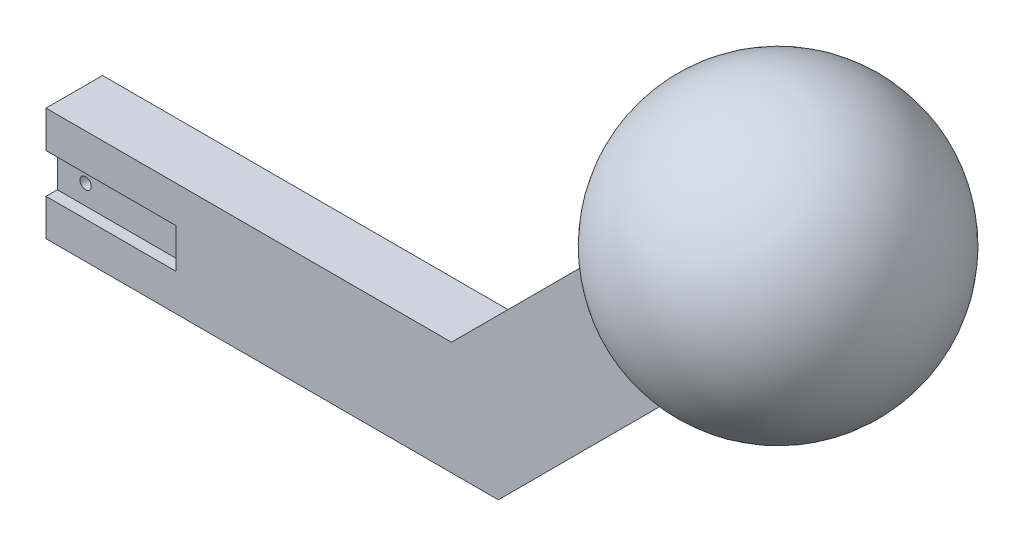
SolidWorks part; units mm, degrees
ref_plane "Front Plane" through (0, 0, 0) normal (0, 0, 1) x (1, 0, 0)
ref_plane "Top Plane" through (0, 0, 0) normal (0, 1, 0) x (1, 0, 0)
ref_plane "Right Plane" through (0, 0, 0) normal (1, 0, 0) x (0, 0, -1)
sketch "Sketch1" plane through (0, 0, 0) normal (0, 0, 1) x (1, 0, 0)
  line L0 (0, 0) -> (80, 0)
  line L1 (80, 0) -> (115.3553, 35.3553)
  line L2 (115.3553, 35.3553) -> (101.2132, 49.4975)
  line L3 (101.2132, 49.4975) -> (71.7157, 20)
  line L4 (71.7157, 20) -> (0, 20)
  line L5 (0, 20) -> (0, 0)
  circle A1 centre (5, 10) radius 1
  dimension "D6" = 10
  dimension "D7" = 5
  dimension "D8" = 2
  dimension "D1" = 20
  dimension "D2" = 20
  dimension "D3" = 135
  dimension "D4" = 80
  dimension "D5" = 50
extrude "Boss-Extrude1" add sketch "Sketch1" along normal blind 10
ref_plane "Plane1" through (0, 0, 5) normal (0, 0, 1) x (1, 0, 0)
sketch "Sketch2" plane through (0, 0, 5) normal (0, 0, 1) x (1, 0, 0)
  line L0 (115.3553, 35.3553) -> (101.2132, 49.4975) construction
  line L1 (115.3553, 35.3553) -> (108.2843, 42.4264) construction
  line L2 (108.2843, 42.4264) -> (142.1638, 76.3059)
  line L3 (108.2843, 42.4264) -> (115.3553, 35.3553)
  line L4 (115.3553, 35.3553) -> (101.2132, 49.4975) construction
  arc A0 (142.1638, 76.3059) -> (115.3553, 35.3553) centre (124.4861, 58.6283) cw
  point P0 (108.2843, 42.4264)
  point P2 (111.8198, 38.8909)
  dimension "D1" = 25
revolve "Revolve2" add sketch "Sketch2" angle 360 about L2
sketch "Sketch4" plane through (0, 0, 0) normal (0, 0, -1) x (-1, 0, 0)
  line L0 (0, 20) -> (0, 0) construction
  line L1 (0, 13.5) -> (-23, 13.5)
  line L2 (0, 13.5) -> (0, 6.5)
  line L3 (0, 6.5) -> (-23, 6.5)
  line L4 (-23, 13.5) -> (-23, 6.5)
  circle A0 centre (-5, 10) radius 1 construction
  dimension "D1" = 7
  dimension "D2" = 3.5
  dimension "D3" = 23
extrude "Cut-Extrude2" [suppressed] cut sketch "Sketch4" against normal blind 2
sketch "Sketch5" plane through (0, 0, 10) normal (0, 0, 1) x (1, 0, 0)
  line L4 (23, 13.5) -> (0, 13.5)
  line L5 (23, 6.5) -> (23, 13.5)
  line L6 (0, 6.5) -> (23, 6.5)
  line L7 (0, 13.5) -> (0, 6.5)
  line L8 (23, 13.5) -> (0, 13.5)
  line L9 (23, 6.5) -> (23, 13.5)
  line L10 (0, 6.5) -> (23, 6.5)
  line L11 (0, 13.5) -> (0, 6.5)
  dimension "D1" = 0
extrude "Cut-Extrude3" cut sketch "Sketch5" against normal blind 2
